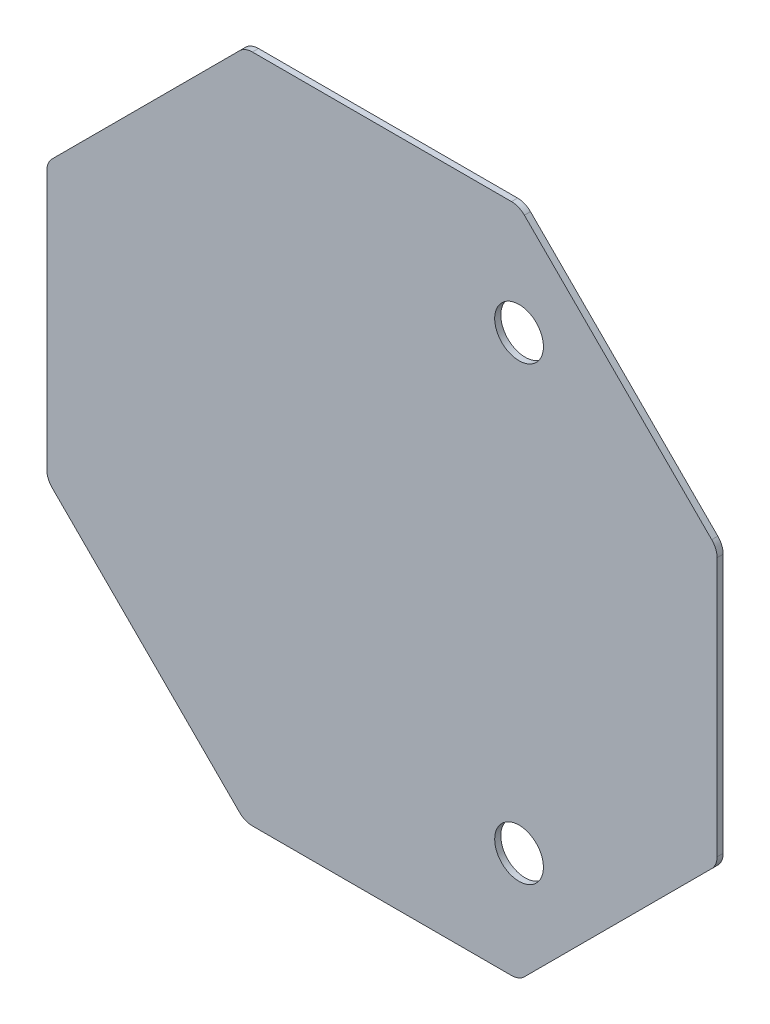
SolidWorks part; units mm, degrees
ref_plane "Front Plane" through (0, 0, 0) normal (0, 0, 1) x (1, 0, 0)
ref_plane "Top Plane" through (0, 0, 0) normal (0, 1, 0) x (1, 0, 0)
ref_plane "Right Plane" through (0, 0, 0) normal (1, 0, 0) x (0, 0, -1)
sketch "Sketch3" plane through (0, 0, 0) normal (0, 0, 1) x (1, 0, 0)
  line L0 (55, -21.2574) -> (55, 21.2574)
  line L1 (-55, 55) -> (55, 55) construction
  line L2 (-55, 55) -> (-55, -55) construction
  line L3 (-55, -55) -> (55, -55) construction
  line L4 (55, 55) -> (55, -55) construction
  line L5 (0, 59.9023) -> (0, -65.6121) construction
  line L6 (-89.0842, 0) -> (87.9232, 0) construction
  line L7 (-55, -21.2574) -> (-55, 21.2574)
  line L8 (-21.2574, -55) -> (21.2574, -55)
  line L9 (23.3787, -54.1213) -> (54.1213, -23.3787)
  line L10 (-21.2574, 55) -> (21.2574, 55)
  line L11 (23.3787, 54.1213) -> (54.1213, 23.3787)
  line L12 (-23.3787, 54.1213) -> (-54.1213, 23.3787)
  line L13 (-54.1213, -23.3787) -> (-23.3787, -54.1213)
  circle A0 centre (22.5, 37) radius 4
  circle A1 centre (22.5, -37) radius 4
  arc A2 (-54.1213, 23.3787) -> (-55, 21.2574) centre (-52, 21.2574) ccw
  arc A3 (-55, -21.2574) -> (-54.1213, -23.3787) centre (-52, -21.2574) ccw
  arc A4 (-23.3787, -54.1213) -> (-21.2574, -55) centre (-21.2574, -52) ccw
  arc A5 (21.2574, -55) -> (23.3787, -54.1213) centre (21.2574, -52) ccw
  arc A6 (54.1213, -23.3787) -> (55, -21.2574) centre (52, -21.2574) ccw
  arc A7 (55, 21.2574) -> (54.1213, 23.3787) centre (52, 21.2574) ccw
  arc A8 (23.3787, 54.1213) -> (21.2574, 55) centre (21.2574, 52) ccw
  arc A9 (-23.3787, 54.1213) -> (-21.2574, 55) centre (-21.2574, 52) cw
  point P23 (-55, 22.5)
  point P26 (-55, -22.5)
  point P29 (-22.5, -55)
  point P32 (22.5, -55)
  point P35 (55, -22.5)
  point P38 (55, 22.5)
  point P41 (22.5, 55)
  point P44 (-22.5, 55)
  dimension "D11" = 8
  dimension "D12" = 3
  dimension "D1" = 110
  dimension "D2" = 55
  dimension "D3" = 110
  dimension "D4" = 55
  dimension "D5" = 22.5
  dimension "D6" = 45
  dimension "D7" = 45
  dimension "D8" = 22.5
  dimension "D9" = 37
  dimension "D10" = 22.5
extrude "Boss-Extrude1" add sketch "Sketch3" along normal blind 1
sketch "Sketch4" plane through (0, 0, 1) normal (0, 0, 1) x (1, 0, 0)
  circle A1 centre (0, 0) radius 50.75 construction
  dimension "D2" = 101.5
